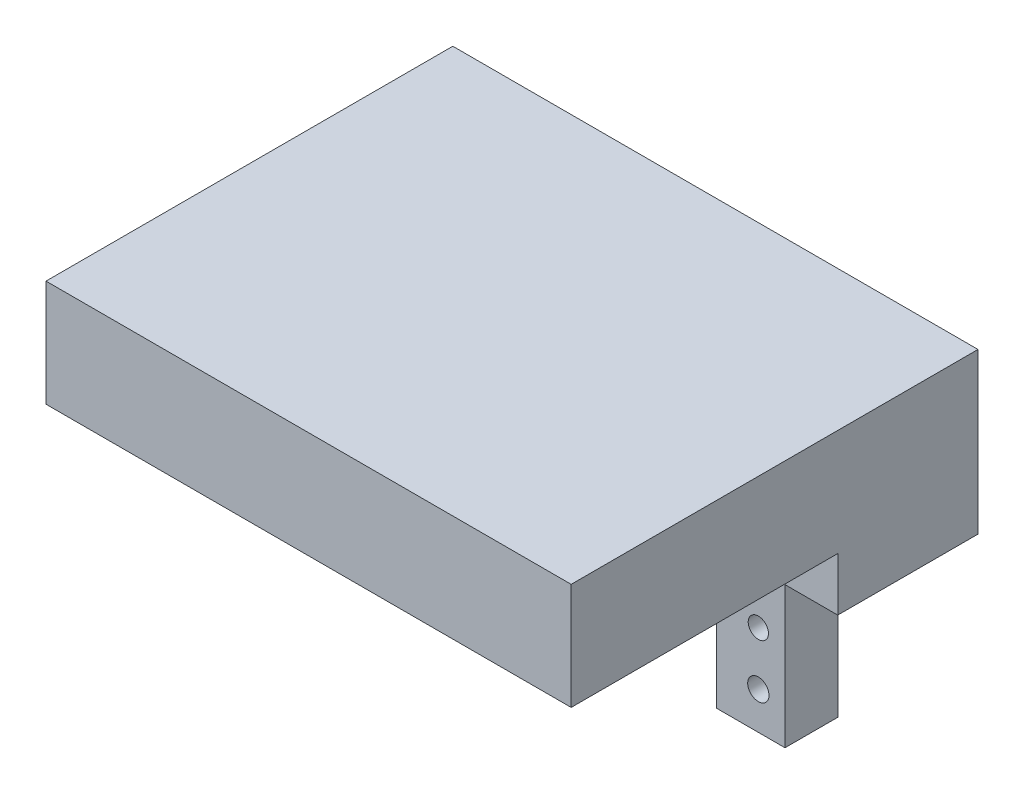
SolidWorks part; units mm, degrees
ref_plane "Front Plane" through (0, 0, 0) normal (0, 0, 1) x (1, 0, 0)
ref_plane "Top Plane" through (0, 0, 0) normal (0, 1, 0) x (1, 0, 0)
ref_plane "Right Plane" through (0, 0, 0) normal (1, 0, 0) x (0, 0, -1)
sketch "Sketch1" plane through (0, 0, 0) normal (0, 1, 0) x (1, 0, 0)
  line L1 (-11.4021, 5.619) -> (13.6169, 5.619)
  line L2 (-11.4021, 5.619) -> (-11.4021, -1.0612)
  line L3 (-11.4021, -1.0612) -> (13.6169, -1.0612)
  line L4 (13.6169, 5.619) -> (13.6169, -1.0612)
  dimension "D1" = 25.019
  dimension "D2" = 6.6802
extrude "Boss-Extrude1" add sketch "Sketch1" along normal blind 7.62
sketch "Sketch2" plane through (0, 0, 0) normal (0, -1, 0) x (1, 0, 0)
  line L6 (-8.8987, -2.259) -> (11.0911, -2.259) construction
  line L12 (1.0962, -3.0845) -> (1.0962, -1.4335) construction
  line L13 (-8.8875, -3.1044) -> (11.1023, -3.1044)
  line L14 (-8.8875, -3.1044) -> (-8.8875, -1.4534)
  line L15 (-8.8875, -1.4534) -> (11.1023, -1.4534)
  line L16 (11.1023, -3.1044) -> (11.1023, -1.4534)
  line L17 (-8.8875, -3.1044) -> (11.1023, -1.4534) construction
  line L18 (-8.8875, -1.4534) -> (11.1023, -3.1044) construction
  point P10 (1.1074, -2.2789)
  dimension "D1" = 19.9898
  dimension "D2" = 1.651
extrude "Cut-Extrude1" cut sketch "Sketch2" against normal blind 1.778
sketch "Sketch5" plane through (0, 0, 0) normal (0, -1, 0) x (1, 0, 0)
  line L0 (-11.4021, 1.0612) -> (13.6169, 1.0612) construction
  line L1 (-8.8875, -1.4534) -> (11.1023, -1.4534)
  line L2 (-8.8875, -1.4534) -> (-8.8875, 1.0612)
  line L3 (-8.8875, 1.0612) -> (11.1023, 1.0612)
  line L4 (11.1023, -1.4534) -> (11.1023, 1.0612)
extrude "Boss-Extrude2" add sketch "Sketch5" along normal blind 6.731
sketch "Sketch7" plane through (0, 0, 1.0612) normal (0, 0, 1) x (1, 0, 0)
  line L0 (-11.4021, 0) -> (13.6169, 0) construction
  line L1 (11.1023, -6.731) -> (-8.8875, -6.731) construction
  line L2 (-0.2515, -6.731) -> (7.8511, -6.731)
  line L3 (-0.2515, -6.731) -> (-0.2515, 0)
  line L4 (-0.2515, 0) -> (7.8511, 0)
  line L5 (7.8511, -6.731) -> (7.8511, 0)
  line L6 (11.1023, -6.731) -> (11.1023, 0) construction
  line L7 (-8.8875, -6.731) -> (-8.8875, 0) construction
  dimension "D1" = 3.2512
  dimension "D2" = 8.636
extrude "Cut-Extrude2" cut sketch "Sketch7" against normal up to next and the other way through all
sketch "Sketch8" plane through (0, 0, 1.0612) normal (0, 0, 1) x (1, 0, 0)
  line L0 (-11.4021, 0) -> (13.6169, 0) construction
  line L1 (-8.8875, 0) -> (-8.8875, 7.62) construction
  line L2 (-11.4021, 7.62) -> (13.6169, 7.62) construction
  line L3 (11.1023, 0) -> (11.1023, 7.62) construction
  line L4 (-8.8875, -6.731) -> (-8.8875, 0) construction
  line L5 (-8.8875, 1.778) -> (11.1023, 1.778) construction
  line L6 (11.1023, -6.731) -> (11.1023, 0) construction
  circle A0 centre (-6.3475, -0.762) radius 1.5748
  circle A1 centre (9.8323, -2.413) radius 0.4826
  circle A2 centre (9.8323, -4.953) radius 0.508
  dimension "D1" = 3.1496
  dimension "D6" = 0.9652
  dimension "D9" = 1.016
  dimension "D2" = 2.54
  dimension "D3" = 2.54
  dimension "D4" = 4.191
  dimension "D5" = 1.27
  dimension "D7" = 2.54
  dimension "D8" = 1.27
extrude "Cut-Extrude5" cut sketch "Sketch8" against normal up to next
sketch "Sketch9" plane through (0, 0, 1.0612) normal (0, 0, 1) x (1, 0, 0)
  line L0 (-8.8875, 0) -> (-8.8875, 7.62) construction
  line L1 (-11.4021, 7.62) -> (13.6169, 7.62) construction
  line L2 (11.1023, 0) -> (11.1023, 7.62) construction
  line L3 (-8.8875, 1.778) -> (11.1023, 1.778) construction
  line L4 (7.8511, 0) -> (-0.2515, 0) construction
  line L5 (13.6169, 7.62) -> (13.6169, 0) construction
  line L6 (-11.4021, 7.62) -> (13.6169, 7.62)
  line L7 (-11.4021, 7.62) -> (-11.4021, 2.54)
  line L8 (-11.4021, 2.54) -> (13.6169, 2.54)
  line L9 (13.6169, 7.62) -> (13.6169, 2.54)
  dimension "D1" = 1.778
  dimension "D2" = 5.08
extrude "Boss-Extrude3" add sketch "Sketch9" along normal blind 12.7
